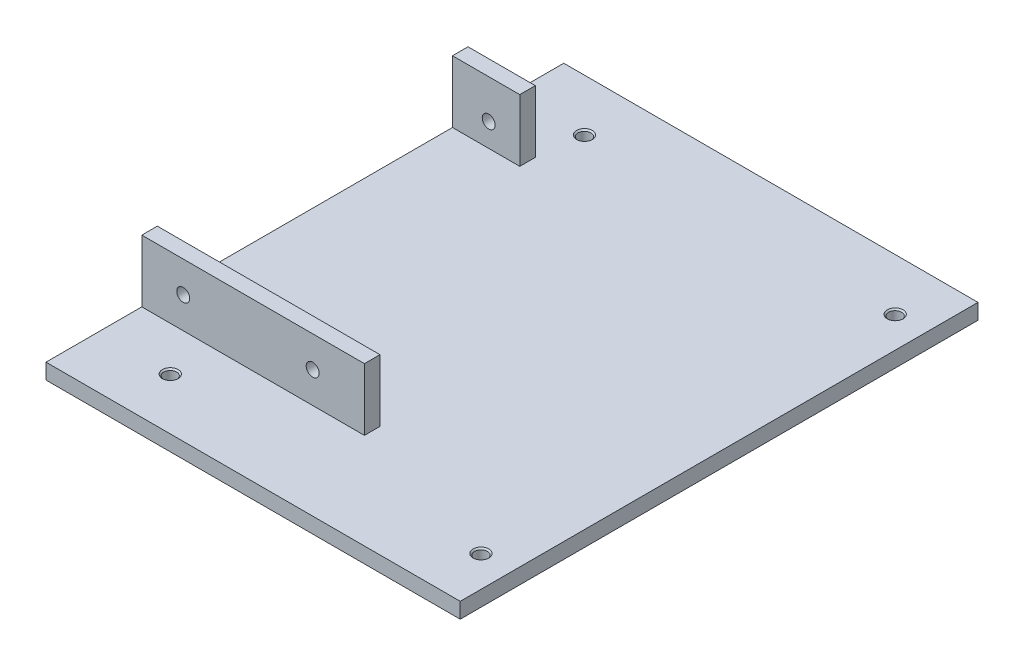
SolidWorks part; units mm, degrees
ref_plane "前视基准面" through (0, 0, 0) normal (0, 0, 1) x (1, 0, 0)
ref_plane "上视基准面" through (0, 0, 0) normal (0, 1, 0) x (1, 0, 0)
ref_plane "右视基准面" through (0, 0, 0) normal (1, 0, 0) x (0, 0, -1)
sketch "草图1" plane through (0, 0, 0) normal (0, 1, 0) x (1, 0, 0)
  line L1 (-60.7657, 28.3376) -> (19.2343, 28.3376)
  line L2 (-60.7657, 28.3376) -> (-60.7657, -71.6624)
  line L3 (-60.7657, -71.6624) -> (19.2343, -71.6624)
  line L4 (19.2343, 28.3376) -> (19.2343, -71.6624)
  dimension "D1" = 100
  dimension "D2" = 80
extrude "凸台-拉伸1" add sketch "草图1" along normal blind 3 contours L2 L3 L4 L1
sketch "草图2" plane through (0, 3, 0) normal (0, 1, 0) x (1, 0, 0)
  line L0 (-60.7657, -21.6624) -> (19.2343, -21.6624) construction
  line L1 (-111.7657, 3.8376) -> (-20.7657, 3.8376)
  line L2 (-111.7657, 3.8376) -> (-111.7657, -47.1624)
  line L3 (-111.7657, -47.1624) -> (-20.7657, -47.1624)
  line L4 (-20.7657, 3.8376) -> (-20.7657, -47.1624)
  line L5 (-60.7657, 28.3376) -> (-60.7657, -71.6624) construction
  line L6 (19.2343, 28.3376) -> (19.2343, -71.6624) construction
  line L7 (-114.7657, 6.8376) -> (-114.7657, -50.1624)
  line L8 (-114.7657, -50.1624) -> (-17.7657, -50.1624)
  line L9 (-17.7657, 6.8376) -> (-17.7657, -50.1624)
  line L10 (-114.7657, 6.8376) -> (-17.7657, 6.8376)
  dimension "D1" = 51
  dimension "D2" = 40
  dimension "D3" = 51
  dimension "D4" = 3
extrude "凸台-拉伸2" add sketch "草图2" along normal blind 45
sketch "草图3" plane through (0, 0, -3.8376) normal (0, 0, 1) x (1, 0, 0)
  line L0 (-74.7657, 48) -> (-74.7657, 14)
  line L1 (-114.7657, 48) -> (-17.7657, 48) construction
  line L3 (-74.7657, 14) -> (-71.7657, 14)
  line L4 (-71.7657, 14) -> (-71.7657, 48)
  line L5 (-71.7657, 48) -> (-74.7657, 48)
  line L6 (-17.7657, 48) -> (-17.7657, 3) construction
  line L7 (-114.7657, 3) -> (-60.7657, 3) construction
  dimension "D1" = 54
  dimension "D2" = 3
  dimension "D3" = 11
extrude "凸台-拉伸3" add sketch "草图3" along normal blind 51
sketch "草图4" plane through (0, 0, -6.8376) normal (0, 0, -1) x (-1, 0, 0)
  line L0 (17.7657, 3) -> (47.7657, 3)
  line L1 (17.7657, 3) -> (60.7657, 3) construction
  line L2 (47.7657, 3) -> (47.7657, 9)
  line L3 (47.7657, 9) -> (17.7657, 9)
  line L4 (17.7657, 48) -> (17.7657, 3) construction
  line L5 (17.7657, 9) -> (17.7657, 3)
  dimension "D1" = 30
  dimension "D2" = 6
extrude "切除-拉伸2" cut sketch "草图4" against normal blind 50
sketch "草图5" plane through (0, 3, 0) normal (0, -1, 0) x (1, 0, 0)
  line L0 (-111.7657, 47.1624) -> (-111.7657, -3.8376)
  line L1 (-111.7657, -3.8376) -> (-60.7657, -3.8376)
  line L2 (-60.7657, -3.8376) -> (-60.7657, 47.1624)
  line L3 (-60.7657, 47.1624) -> (-111.7657, 47.1624)
  line L4 (-114.7657, 50.1624) -> (-114.7657, -6.8376)
  line L5 (-114.7657, -6.8376) -> (-57.7657, -6.8376)
  line L6 (-57.7657, -6.8376) -> (-57.7657, 50.1624)
  line L7 (-57.7657, 50.1624) -> (-114.7657, 50.1624)
  dimension "D1" = 3
extrude "凸台-拉伸4" add sketch "草图5" along normal blind 30
sketch "草图6" plane through (0, 3, 0) normal (0, 1, 0) x (1, 0, 0)
  line L0 (-60.7657, -21.6624) -> (19.2343, -21.6624) construction
  line L1 (-60.7657, 3.8376) -> (-60.7657, -47.1624) construction
  line L2 (19.2343, 28.3376) -> (19.2343, -71.6624) construction
  line L3 (-60.7657, 28.3376) -> (-60.7657, 6.8376) construction
  line L4 (-60.7657, 28.3376) -> (19.2343, 28.3376) construction
  point P0 (-46.7657, 18.3376)
  point P1 (-46.7657, -61.6624)
  point P8 (13.2343, -61.6624)
  point P13 (13.2343, 18.3376)
  dimension "D1" = 14
  dimension "D2" = 10
  dimension "D3" = 10
  dimension "D4" = 60
hole_wizard "M3 螺纹孔1" positions "草图7" profile "草图8" tap size "M3" standard "GB" end condition through all
sketch "草图7" plane through (0, 3, 0) normal (0, 1, 0) x (1, 0, 0)
  point P0 (-46.7657, 18.3376)
  point P3 (13.2343, 18.3376)
  point P6 (13.2343, -61.6624)
  point P9 (-46.7657, -61.6624)
sketch "草图8" plane through (-46.7657, 3, -18.3376) normal (1, 0, 0) x (0, 0, 1)
  line L0 (0, 0) -> (0, 30)
  line L1 (0, 30) -> (1.25, 30)
  line L2 (1.25, 30) -> (1.25, 0.275)
  line L3 (1.25, 0.275) -> (1.525, 0)
  line L5 (1.525, 0) -> (0, 0)
  line L6 (-1.25, 0.275) -> (-1.525, 0) construction
  line L11 (0, -6.35) -> (0, 107.95) construction
  dimension "通孔螺纹孔钻头直径" = 2.5
  dimension "通孔螺纹孔钻头深度" = 30
  dimension "近端锥形沉头孔直径" = 3.05
  dimension "近端锥形沉头孔角度" = 90
cosmetic thread "孔螺蚊线1" parameters "D2"=3
cosmetic thread "孔螺蚊线2" parameters "D2"=3
cosmetic thread "孔螺蚊线3" parameters "D2"=3
cosmetic thread "孔螺蚊线4" parameters "D2"=3
sketch "草图9" plane through (0, -27, 0) normal (0, -1, 0) x (-1, 0, 0)
  line L0 (57.7657, -50.1624) -> (114.7657, -50.1624) construction
  line L1 (60.7657, -50.1624) -> (57.7657, -50.1624)
  line L2 (60.7657, -50.1624) -> (60.7657, 6.8376)
  line L3 (60.7657, 6.8376) -> (57.7657, 6.8376)
  line L4 (57.7657, -50.1624) -> (57.7657, 6.8376)
  line L5 (57.7657, 6.8376) -> (60.7657, 6.8376) construction
  line L6 (114.7657, 6.8376) -> (57.7657, 6.8376) construction
  dimension "D1" = 3
extrude "切除-拉伸3" cut sketch "草图9" against normal blind 27
sketch "草图10" plane through (-17.7657, 0, 0) normal (1, 0, 0) x (0, 0, -1)
  line L0 (-43.1624, 3) -> (-43.1624, 11)
  line L1 (-43.1624, 11) -> (6.8376, 11)
  line L2 (6.8376, 48) -> (6.8376, 9) construction
  line L3 (6.8376, 11) -> (6.8376, 3)
  line L4 (28.3376, 3) -> (-71.6624, 3) construction
  line L5 (6.8376, 3) -> (-43.1624, 3)
  dimension "D1" = 8
extrude "切除-拉伸4" cut sketch "草图10" against normal blind 30
sketch "草图14" plane through (0, 0, 50.1624) normal (0, 0, 1) x (1, 0, 0)
  line L0 (-17.7657, 48) -> (-17.7657, 3) construction
  line L1 (-60.7657, 3) -> (-17.7657, 3) construction
  point P0 (-52.7657, 9)
  point P1 (-27.7657, 9)
  dimension "D1" = 10
  dimension "D2" = 35
  dimension "D3" = 6
  dimension "D4" = 6
sketch "草图17" plane through (0, 0, -6.8376) normal (0, 0, -1) x (-1, 0, 0)
  line L0 (47.7657, 3) -> (47.7657, 11) construction
  line L1 (47.7657, 3) -> (60.7657, 3) construction
  point P0 (53.7657, 7.5)
  point P1 (44.7152, -4.3762)
  dimension "D1" = 6
  dimension "D2" = 4.5
hole_wizard "M3 螺纹孔3" positions "草图18" profile "草图19" tap size "M3" standard "GB"
sketch "草图18" plane through (0, 0, -6.8376) normal (0, 0, -1) x (-1, 0, 0)
  point P0 (53.7657, 7.5)
sketch "草图19" plane through (-53.7657, 7.5, -6.8376) normal (1, 0, 0) x (0, 1, 0)
  line L0 (0, 0) -> (0, 3)
  line L1 (0, 3) -> (1.25, 3)
  line L2 (1.25, 3) -> (1.25, 0)
  line L5 (1.25, 0) -> (0, 0)
  line L11 (0, -6.35) -> (0, 107.95) construction
  dimension "通孔螺纹孔钻头直径" = 2.5
  dimension "通孔螺纹孔钻头深度" = 3
cosmetic thread "孔螺蚊线7" parameters "D2"=3
hole_wizard "M3 螺纹孔4" positions "草图21" profile "草图22" tap size "M3" standard "GB"
sketch "草图21" plane through (0, 0, 50.1624) normal (0, 0, 1) x (1, 0, 0)
  point P0 (-52.7657, 9)
  point P3 (-27.7657, 9)
sketch "草图22" plane through (-52.7657, 9, 50.1624) normal (1, 0, 0) x (0, -1, 0)
  line L0 (0, 0) -> (0, 3)
  line L1 (0, 3) -> (1.25, 3)
  line L2 (1.25, 3) -> (1.25, 0)
  line L5 (1.25, 0) -> (0, 0)
  line L11 (0, -6.35) -> (0, 107.95) construction
  dimension "通孔螺纹孔钻头直径" = 2.5
  dimension "通孔螺纹孔钻头深度" = 3
cosmetic thread "孔螺蚊线8" parameters "D2"=3
cosmetic thread "孔螺蚊线9" parameters "D2"=3
sketch "草图23" plane through (0, 0, 50.1624) normal (0, 0, 1) x (1, 0, 0)
  line L1 (-17.7657, 3) -> (-60.7657, 3)
  line L2 (-17.7657, 3) -> (-17.7657, 15)
  line L3 (-17.7657, 15) -> (-60.7657, 15)
  line L4 (-60.7657, 3) -> (-60.7657, 15)
  line L5 (-60.7657, 3) -> (-60.7657, 0) construction
  dimension "D1" = 12
extrude "凸台-拉伸8" add sketch "草图23" along normal blind 3 separate body
sketch "草图27" plane through (0, 0, 53.1624) normal (0, 0, 1) x (1, 0, 0)
  point P0 (-52.7657, 9)
  point P1 (-27.7657, 9)
sketch "草图28" plane through (0, 0, -6.8376) normal (0, 0, -1) x (-1, 0, 0)
  line L0 (47.7657, 3) -> (47.7657, 11) construction
  line L1 (60.7657, 3) -> (47.7657, 3)
  line L2 (60.7657, 3) -> (60.7657, 15)
  line L3 (60.7657, 15) -> (47.7657, 15)
  line L4 (47.7657, 3) -> (47.7657, 15)
  dimension "D1" = 12
extrude "凸台-拉伸9" add sketch "草图28" along normal blind 3 separate body contours L4 L3 L2 L1
sketch "草图30" plane through (0, 0, -9.8376) normal (0, 0, -1) x (-1, 0, 0)
  point P0 (53.7657, 7.5)
sketch "草图31" plane through (-17.7657, 0, 0) normal (1, 0, 0) x (0, 0, -1)
  line L1 (-50.1624, 48) -> (6.8376, 48)
  line L2 (-50.1624, 48) -> (-50.1624, 3)
  line L3 (-50.1624, 3) -> (6.8376, 3)
  line L4 (6.8376, 48) -> (6.8376, 3)
extrude "切除-拉伸5" cut sketch "草图31" against normal through all
sketch "草图32" plane through (0, 3, 0) normal (0, 1, 0) x (1, 0, 0)
  line L1 (-114.7657, 6.8376) -> (-60.7657, 6.8376)
  line L2 (-114.7657, 6.8376) -> (-114.7657, -50.1624)
  line L3 (-114.7657, -50.1624) -> (-60.7657, -50.1624)
  line L4 (-60.7657, 6.8376) -> (-60.7657, -50.1624)
extrude "切除-拉伸6" cut sketch "草图32" against normal through all
hole_wizard "M3 螺纹孔5" positions "草图36" profile "草图37" tap size "M3" standard "GB" end condition up to next
sketch "草图36" plane through (0, 0, 53.1624) normal (0, 0, 1) x (1, 0, 0)
  point P0 (-52.7657, 9)
  point P3 (-27.7657, 9)
sketch "草图37" plane through (-52.7657, 9, 53.1624) normal (1, 0, 0) x (0, -1, 0)
  line L0 (0, 0) -> (0, 3)
  line L1 (0, 3) -> (1.25, 3)
  line L2 (1.25, 3) -> (1.25, 0)
  line L5 (1.25, 0) -> (0, 0)
  line L11 (0, -6.35) -> (0, 107.95) construction
  dimension "通孔螺纹孔钻头直径" = 2.5
  dimension "通孔螺纹孔钻头深度" = 3
cosmetic thread "孔螺蚊线10" parameters "D2"=3
cosmetic thread "孔螺蚊线11" parameters "D2"=3
hole_wizard "M3 螺纹孔6" positions "草图38" profile "草图39" tap size "M3" standard "GB" end condition up to next
sketch "草图38" plane through (0, 0, -9.8376) normal (0, 0, -1) x (-1, 0, 0)
  point P0 (53.7657, 7.5)
sketch "草图39" plane through (-53.7657, 7.5, -9.8376) normal (1, 0, 0) x (0, 1, 0)
  line L0 (0, 0) -> (0, 3)
  line L1 (0, 3) -> (1.25, 3)
  line L2 (1.25, 3) -> (1.25, 0)
  line L5 (1.25, 0) -> (0, 0)
  line L11 (0, -6.35) -> (0, 107.95) construction
  dimension "通孔螺纹孔钻头直径" = 2.5
  dimension "通孔螺纹孔钻头深度" = 3
cosmetic thread "孔螺蚊线12" parameters "D2"=3
